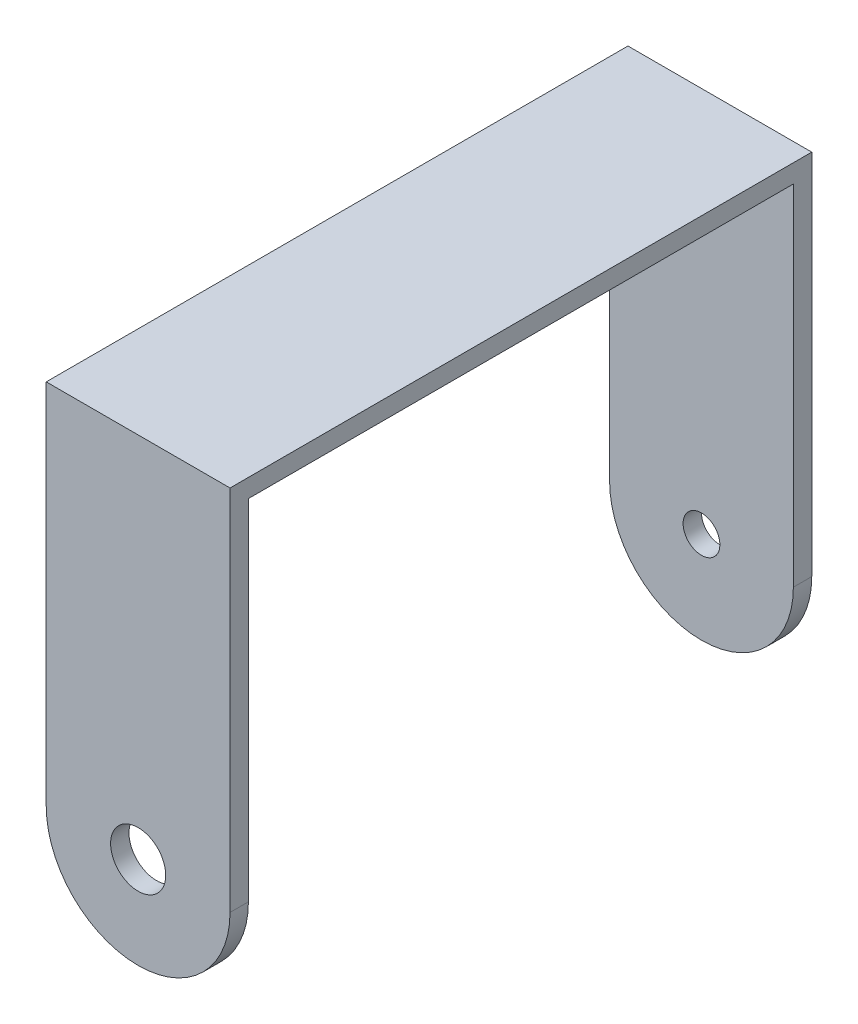
SolidWorks part; units mm, degrees
ref_plane "前视基准面" through (0, 0, 0) normal (0, 0, 1) x (1, 0, 0)
ref_plane "上视基准面" through (0, 0, 0) normal (0, 1, 0) x (1, 0, 0)
ref_plane "右视基准面" through (0, 0, 0) normal (1, 0, 0) x (0, 0, -1)
sketch "草图1" plane through (0, 0, 0) normal (0, 0, 1) x (1, 0, 0)
  line L2 (0, 0) -> (0, 40)
  line L3 (0, 40) -> (20, 40)
  line L4 (20, 0) -> (20, 40)
  arc A0 (20, 0) -> (0, 0) centre (10, 0) cw
  dimension "D1" = 20
  dimension "D2" = 40
extrude "凸台-拉伸1" add sketch "草图1" along normal blind 2
sketch "草图2" plane through (0, 0, 2) normal (0, 0, 1) x (1, 0, 0)
  line L0 (20, 0) -> (20, 40) construction
  line L1 (0, 40) -> (20, 40)
  line L2 (0, 40) -> (0, 38)
  line L3 (0, 38) -> (20, 38)
  line L4 (20, 40) -> (20, 38)
  dimension "D1" = 2
extrude "凸台-拉伸2" add sketch "草图2" along normal blind 61.3
sketch "草图3" plane through (0, 40, 0) normal (0, 1, 0) x (1, 0, 0)
  line L0 (0, -31.65) -> (20, -31.65) construction
  line L1 (0, -63.3) -> (0, 0) construction
  line L2 (20, -63.3) -> (20, 0) construction
ref_plane "基准面1" through (0, 0, 31.65) normal (0, 0, 1) x (1, 0, 0)
mirror "镜向1" about plane through (0, 0, 31.65) normal (0, 0, 1) of "凸台-拉伸1"
sketch "草图4" plane through (0, 0, 63.3) normal (0, 0, 1) x (1, 0, 0)
  line L0 (20, 0) -> (0, 0) construction
  circle A0 centre (10, 0) radius 3
  dimension "D1" = 6
  dimension "D2" = 10
extrude "切除-拉伸1" cut sketch "草图4" against normal up to next
sketch "草图5" plane through (0, 0, 0) normal (0, 0, -1) x (-1, 0, 0)
  line L0 (0, 0) -> (-20, 0) construction
  line L1 (-10, 0) -> (-10, -10) construction
  arc A0 (-20, 0) -> (0, 0) centre (-10, 0) ccw construction
  circle A1 centre (-10, -7) radius 1.65
  circle A2 centre (-17, 0) radius 1.65
  circle A3 centre (-10, 7) radius 1.65
  circle A4 centre (-3, 0) radius 1.65
  point P20 (-10, 0)
  dimension "D1" = 3.3
  dimension "D2" = 7
  dimension "D3" = 4
sketch "草图6" plane through (0, 0, 2) normal (0, 0, 1) x (1, 0, 0)
  circle A0 centre (10, 0) radius 2
extrude "切除-拉伸2" cut sketch "草图6" against normal blind 2
